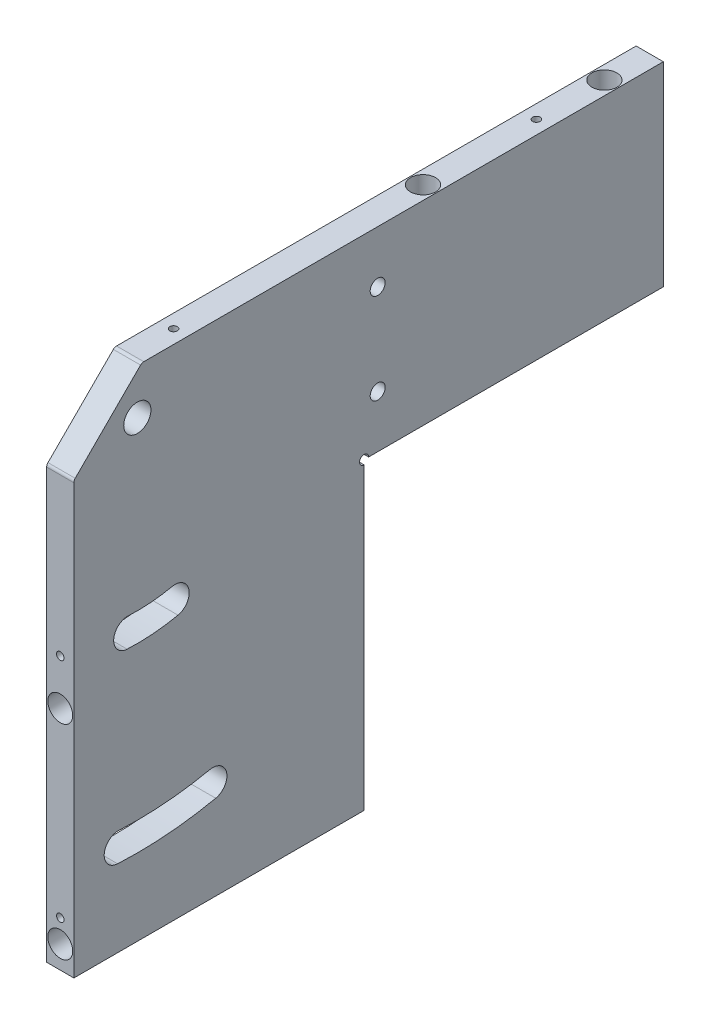
SolidWorks part; units mm, degrees
material "6061"
ref_plane "前视" through (0, 0, 0) normal (0, 0, 1) x (1, 0, 0)
ref_plane "上视" through (0, 0, 0) normal (0, 1, 0) x (1, 0, 0)
ref_plane "右视" through (0, 0, 0) normal (1, 0, 0) x (0, 0, -1)
sketch "草图1" plane through (0, 0, 0) normal (1, 0, 0) x (0, 0, -1)
  line L1 (-130, -110) -> (130, -110)
  line L2 (-130, -110) -> (-130, 110)
  line L3 (-130, 110) -> (130, 110)
  line L4 (130, -110) -> (130, 110)
  line L5 (-130, -110) -> (130, 110) construction
  line L6 (-130, 110) -> (130, -110) construction
  point P0 (0, 0)
  dimension "D1" = 260
  dimension "D2" = 220
extrude "凸台-拉伸1" add sketch "草图1" along normal mid plane 12
sketch "草图4" plane through (6, 0, 0) normal (1, 0, 0) x (0, 0, -1)
  line L1 (130, -110) -> (-2, -110)
  line L2 (130, -110) -> (130, 24)
  line L3 (130, 24) -> (-2, 24)
  line L4 (-2, -110) -> (-2, 24)
  line L5 (130, 110) -> (-130, 110) construction
  line L6 (130, -110) -> (130, 110) construction
  dimension "D1" = 86
  dimension "D2" = 132
extrude "切除-拉伸1" cut sketch "草图4" against normal through all
hole_wizard "打孔尺寸根据内六角圆柱头螺钉的类型1" positions "草图3" profile "草图2" counterbore size "M6" standard "Gb" end condition through all
sketch "草图3" plane through (-6, -19.9449, 4.6226) normal (1, 0, 0) x (0, 0, -1)
  line L2 (4.6226, 86.9449) -> (134.6226, 86.9449) construction
  line L4 (134.6226, 43.9449) -> (134.6226, 129.9449) construction
  line L5 (2.6226, 43.9449) -> (2.6226, -90.0551) construction
  point P0 (8.6226, 106.9449)
  point P15 (8.6226, 66.9449)
  dimension "D1" = 40
  dimension "D2" = 6
sketch "草图2" plane through (-6, 87, -4) normal (0, 1, 0) x (0, 0, 1)
  line L0 (0, 0) -> (0, 12)
  line L1 (0, 12) -> (3.3, 12)
  line L3 (3.3, 12) -> (3.3, 6.8)
  line L4 (3.3, 6.8) -> (5.5, 6.8)
  line L5 (5.5, 6.8) -> (5.5, 0)
  line L7 (5.5, 0) -> (0, 0)
  line L11 (0, -6.35) -> (0, 107.95) construction
  dimension "通孔孔直径" = 6.6
  dimension "通孔孔深度" = 12
  dimension "柱形沉头孔直径" = 11
  dimension "柱形沉头孔深度" = 6.8
hole_wizard "M12 间隙孔1" positions "草图6" profile "草图5" hole size "M12" standard "Gb" end condition through all
sketch "草图6" plane through (-6, 0, 0) normal (-1, 0, 0) x (0, 0, 1)
  line L1 (-130, 110) -> (130, 110) construction
  line L2 (2, 24) -> (2, -110) construction
  point P0 (102, 90)
  dimension "D1" = 100
  dimension "D2" = 20
sketch "草图5" plane through (-6, 90, 102) normal (0, 1, 0) x (0, 0, 1)
  line L0 (0, 0) -> (0, 12)
  line L1 (0, 12) -> (6, 12)
  line L2 (6, 12) -> (6, 0)
  line L5 (6, 0) -> (0, 0)
  line L11 (0, -6.35) -> (0, 107.95) construction
  dimension "通孔孔直径" = 12
  dimension "通孔孔深度" = 12
sketch "草图7" plane through (-6, 0, 0) normal (-1, 0, 0) x (0, 0, 1)
  line L0 (102, 90) -> (102, 3.75) construction
  line L1 (102, 90) -> (84.0676, 5.6348) construction
  line L2 (102, 90) -> (110.3738, -69.7807) construction
  line L3 (102, 90) -> (102, -76.25) construction
  line L4 (102, 90) -> (67.4347, -72.617) construction
  circle A0 centre (102, 90) radius 80 construction
  arc A1 (86.6665, 17.8616) -> (105.8598, 16.3511) centre (102, 90) ccw
  arc A2 (84.0676, 5.6348) -> (106.514, 3.8682) centre (102, 90) ccw
  arc A3 (67.4347, -72.617) -> (110.7009, -76.0222) centre (102, 90) ccw
  circle A4 centre (102, 90) radius 160 construction
  arc A5 (70.0336, -60.3902) -> (110.0467, -63.5393) centre (102, 90) ccw
  arc A6 (105.8598, 16.3511) -> (106.514, 3.8682) centre (106.1869, 10.1096) cw
  arc A7 (86.6665, 17.8616) -> (84.0676, 5.6348) centre (85.3671, 11.7482) ccw
  arc A8 (70.0336, -60.3902) -> (67.4347, -72.617) centre (68.7341, -66.5036) ccw
  arc A9 (110.0467, -63.5393) -> (110.7009, -76.0222) centre (110.3738, -69.7807) cw
  dimension "D2" = 12.5
  dimension "D3" = 160
  dimension "D4" = 320
  dimension "D1" = 12
  dimension "D5" = 3
extrude "切除-拉伸2" cut sketch "草图7" against normal through all
hole_wizard "M6 螺纹孔1" positions "草图9" profile "草图8" tap size "M6" standard "Gb"
sketch "草图9" plane through (0, 0, -130) normal (0, 0, -1) x (-1, 0, 0)
  line L0 (0, 110) -> (0, 67) construction
  line L1 (-6, 110) -> (6, 110) construction
  line L2 (0, 67) -> (6, 67) construction
  line L3 (6, 24) -> (6, 110) construction
  point P0 (0, 87)
  point P15 (0, 47)
  dimension "D1" = 40
sketch "草图8" plane through (0, 87, -130) normal (1, 0, 0) x (0, 1, 0)
  line L0 (0, 0) -> (0, 16.5022)
  line L1 (0, 16.5022) -> (2.5, 15)
  line L2 (2.5, 15) -> (2.5, 0)
  line L5 (2.5, 0) -> (0, 0)
  line L10 (0, 16.5022) -> (-2.5, 15) construction
  line L11 (0, -6.35) -> (0, 107.95) construction
  dimension "螺纹孔钻头直径" = 5
  dimension "螺纹孔钻头深度" = 15
  dimension "导头角度" = 118
cosmetic thread "孔螺蚊线1" parameters "D1"=12, "D2"=6
cosmetic thread "孔螺蚊线2" parameters "D1"=12, "D2"=6
hole_wizard "打孔尺寸根据内六角圆柱头螺钉的类型3" positions "草图13" profile "草图12" counterbore size "M6" standard "Gb" end condition through all
sketch "草图13" plane through (4.6436, 65.31, 130) normal (0, 0, -1) x (-1, 0, 0)
  line L0 (4.6436, -41.31) -> (4.6436, -120.31) construction
  line L1 (10.6436, -41.31) -> (-1.3564, -41.31) construction
  line L2 (4.6436, -120.31) -> (10.6436, -120.31) construction
  line L4 (-1.3564, -175.31) -> (10.6436, -175.31) construction
  point P0 (4.6436, -75.31)
  point P15 (4.6436, -165.31)
  point P17 (4.6436, -175.31)
  dimension "D1" = 90
  dimension "D2" = 10
sketch "草图12" plane through (0, -10, 130) normal (1, 0, 0) x (0, -1, 0)
  line L0 (0, 0) -> (0, 260)
  line L1 (0, 260) -> (3.3, 260)
  line L3 (3.3, 260) -> (3.3, 87)
  line L4 (3.3, 87) -> (5.5, 87)
  line L5 (5.5, 87) -> (5.5, 0)
  line L7 (5.5, 0) -> (0, 0)
  line L11 (0, -6.35) -> (0, 107.95) construction
  dimension "通孔孔直径" = 6.6
  dimension "通孔孔深度" = 260
  dimension "柱形沉头孔直径" = 11
  dimension "柱形沉头孔深度" = 87
hole_wizard "打孔尺寸根据内六角圆柱头螺钉的类型2" positions "草图15" profile "草图14" counterbore size "M6" standard "Gb" end condition through all
sketch "草图15" plane through (-2.1961, 110, 22.8573) normal (0, -1, 0) x (-1, 0, 0)
  line L0 (-2.1961, 20.8573) -> (-2.1961, 92.8573) construction
  line L1 (3.8039, 20.8573) -> (-8.1961, 20.8573) construction
  line L2 (-2.1961, 92.8573) -> (-6, 92.8573) construction
  line L4 (3.8039, 152.8573) -> (-8.1961, 152.8573) construction
  point P0 (-2.1961, 52.8573)
  point P14 (-2.1961, 132.8573)
  dimension "D1" = 80
  dimension "D2" = 60
sketch "草图14" plane through (0, 110, -30) normal (1, 0, 0) x (0, 0, 1)
  line L0 (0, 0) -> (0, 220)
  line L1 (0, 220) -> (3.3, 220)
  line L3 (3.3, 220) -> (3.3, 48)
  line L4 (3.3, 48) -> (5.5, 48)
  line L5 (5.5, 48) -> (5.5, 0)
  line L7 (5.5, 0) -> (0, 0)
  line L11 (0, -6.35) -> (0, 107.95) construction
  dimension "通孔孔直径" = 6.6
  dimension "通孔孔深度" = 220
  dimension "柱形沉头孔直径" = 11
  dimension "柱形沉头孔深度" = 48
hole_wizard "孔1" positions "草图11" profile "草图10" legacy end condition through all
sketch "草图11" plane through (-6, 0, 0) normal (-1, 0, 0) x (0, 0, 1)
  line L0 (-130, 24) -> (2, 24) construction
  line L1 (2, 24) -> (2, -110) construction
  point P0 (2, 24)
sketch "草图10" plane through (-6, 24, 2) normal (0, 1, 0) x (0, 0, 1)
  line L0 (0, 0) -> (0, 12)
  line L1 (0, 12) -> (2, 12)
  line L2 (2, 12) -> (2, 0)
  line L3 (2, 0) -> (0, 0)
  line L4 (0, 110) -> (0, -10) construction
  dimension "直径" = 4
  dimension "深度" = 12
hole_wizard "M4 螺纹孔1" positions "草图17" profile "草图16" tap size "M4" standard "Gb"
sketch "草图17" plane through (0, 0, 130) normal (0, 0, 1) x (1, 0, 0)
  line L0 (6, -110) -> (-6, -110) construction
  point P0 (0, -90)
  point P2 (0, 10)
  dimension "D1" = 20
  dimension "D2" = 100
sketch "草图16" plane through (0, -90, 130) normal (1, 0, 0) x (0, -1, 0)
  line L0 (0, 0) -> (0, 11.0914)
  line L1 (0, 11.0914) -> (1.65, 10.1)
  line L2 (1.65, 10.1) -> (1.65, 0)
  line L5 (1.65, 0) -> (0, 0)
  line L10 (0, 11.0914) -> (-1.65, 10.1) construction
  line L11 (0, -6.35) -> (0, 107.95) construction
  dimension "螺纹孔钻头直径" = 3.3
  dimension "螺纹孔钻头深度" = 10.1
  dimension "导头角度" = 118
cosmetic thread "孔螺蚊线3" parameters "D1"=8, "D2"=4
cosmetic thread "孔螺蚊线4" parameters "D1"=8, "D2"=4
hole_wizard "M4 螺纹孔2" positions "草图19" profile "草图18" tap size "M4" standard "Gb"
sketch "草图19" plane through (0, 110, 0) normal (0, 1, 0) x (1, 0, 0)
  line L0 (0, 130) -> (0, 0) construction
  line L1 (6, 130) -> (-6, 130) construction
  line L2 (0, 0) -> (6, 0) construction
  line L3 (6, 130) -> (6, -130) construction
  point P0 (0, 80)
  point P14 (0, -80)
  dimension "D1" = 160
sketch "草图18" plane through (0, 110, -80) normal (1, 0, 0) x (0, 0, 1)
  line L0 (0, 0) -> (0, 11.0914)
  line L1 (0, 11.0914) -> (1.65, 10.1)
  line L2 (1.65, 10.1) -> (1.65, 0)
  line L5 (1.65, 0) -> (0, 0)
  line L10 (0, 11.0914) -> (-1.65, 10.1) construction
  line L11 (0, -6.35) -> (0, 107.95) construction
  dimension "螺纹孔钻头直径" = 3.3
  dimension "螺纹孔钻头深度" = 10.1
  dimension "导头角度" = 118
cosmetic thread "孔螺蚊线5" parameters "D1"=8, "D2"=4
cosmetic thread "孔螺蚊线6" parameters "D1"=8, "D2"=4
chamfer "倒角1" distance 30 angle 45 1 edges at (0, 110, 130)
fillet "圆角1" radius 2 2 edges at (0, 80, 130) (0, 110, 100)
